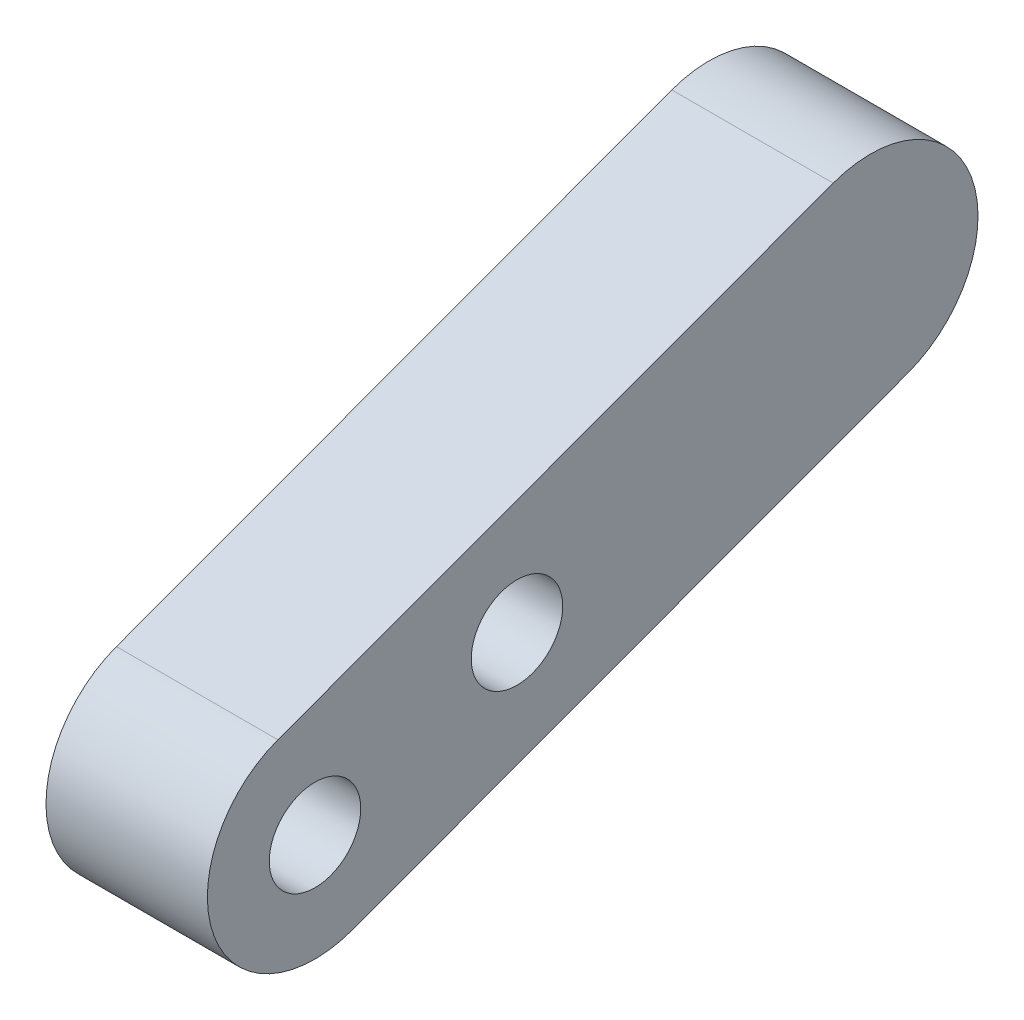
SolidWorks part; units mm, degrees
ref_plane "Front Plane" through (0, 0, 0) normal (0, 0, 1) x (1, 0, 0)
ref_plane "Top Plane" through (0, 0, 0) normal (0, 1, 0) x (1, 0, 0)
ref_plane "Right Plane" through (0, 0, 0) normal (1, 0, 0) x (0, 0, -1)
sketch "Sketch1" plane through (0, 0, 0) normal (1, 0, 0) x (0, 0, -1)
  line L0 (0, 0) -> (-7.5078, -2.7628) construction
  line L1 (0, 0) -> (13.1386, 4.8349) construction
  line L3 (-4.7968, 0.2714) -> (-12.4889, -1.9265) construction
  line L4 (13.1386, 4.8349) -> (-7.5078, -2.7628) construction
  line L5 (14.52, 1.081) -> (-6.1264, -6.5167)
  line L6 (11.7572, 8.5888) -> (-8.8892, 0.9911)
  line L7 (-8.8892, 0.9911) -> (-8.0949, -1.1674) construction
  line L9 (-7.5078, -2.7628) -> (-6.1264, -6.5167) construction
  line L10 (12.5105, 5.2168) -> (11.4116, 9.0628) construction
  circle A0 centre (0, 0) radius 1.7
  circle A1 centre (0, 0) radius 1.7 construction
  arc A2 (14.52, 1.081) -> (11.7572, 8.5888) centre (13.1386, 4.8349) ccw
  arc A3 (-8.8892, 0.9911) -> (-6.1264, -6.5167) centre (-7.5078, -2.7628) ccw
  circle A4 centre (-7.5078, -2.7628) radius 1.7
  point P11 (2.8154, 1.0361)
  dimension "D1" = 2.3
  dimension "D2" = 14
extrude "Boss-Extrude1" add sketch "Sketch1" against normal blind 6
